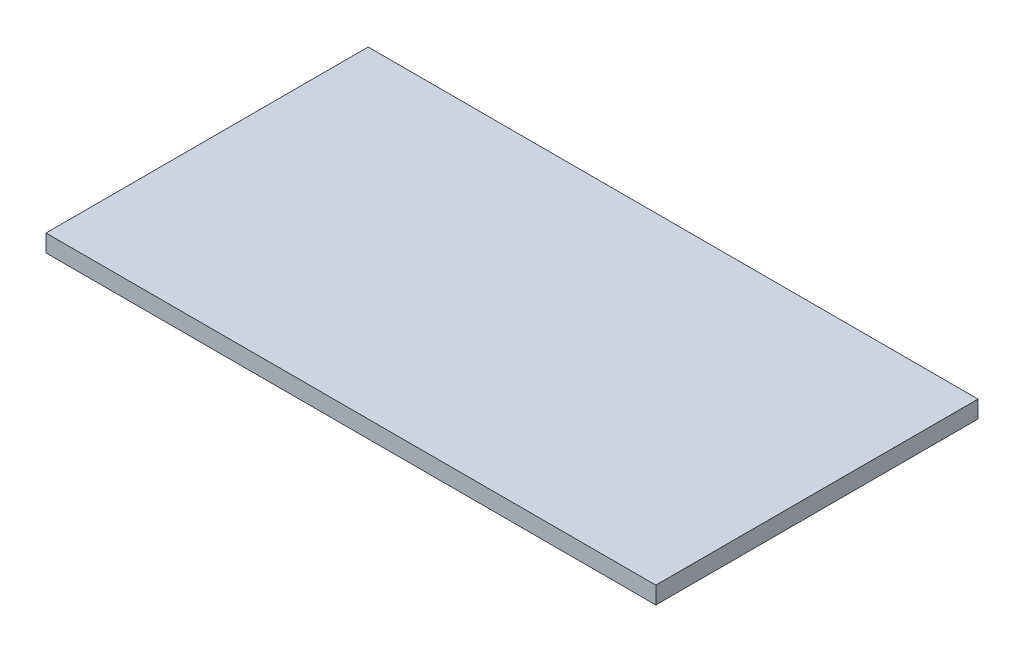
SolidWorks part; units mm, degrees
material "Pine"
ref_plane "Front Plane" through (0, 0, 0) normal (0, 0, 1) x (1, 0, 0)
ref_plane "Top Plane" through (0, 0, 0) normal (0, 1, 0) x (1, 0, 0)
ref_plane "Right Plane" through (0, 0, 0) normal (1, 0, 0) x (0, 0, -1)
sketch "Sketch1" plane through (0, 0, 0) normal (0, 1, 0) x (1, 0, 0)
  line L1 (0, 0) -> (212, 0)
  line L2 (0, 0) -> (0, 112)
  line L3 (0, 112) -> (212, 112)
  line L4 (212, 0) -> (212, 112)
  dimension "D1" = 212
  dimension "D2" = 112
extrude "Boss-Extrude1" add sketch "Sketch1" along normal blind 6
equation "\"BoardThickness\"= 6"
equation "\"D1@Boss-Extrude1\"=\"BoardThickness\""
equation "\"D1@Sketch1\"=200+\"BoardThickness\"*2"
equation "\"D2@Sketch1\"=100+\"BoardThickness\"*2"
